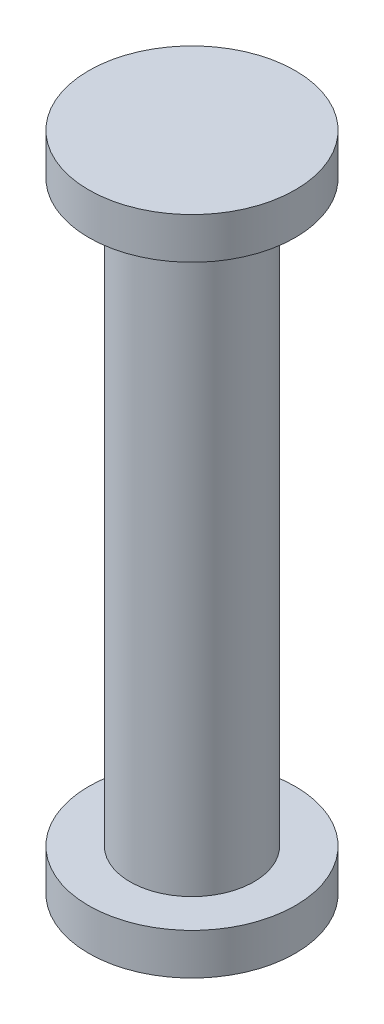
SolidWorks part; units mm, degrees
material "1023 Листовая углеродистая сталь (SS)"
ref_plane "Спереди" through (0, 0, 0) normal (0, 0, 1) x (1, 0, 0)
ref_plane "Сверху" through (0, 0, 0) normal (0, 1, 0) x (1, 0, 0)
ref_plane "Справа" through (0, 0, 0) normal (1, 0, 0) x (0, 0, -1)
sketch "Эскиз1" plane through (0, 0, 0) normal (0, 0, 1) x (1, 0, 0)
  line L0 (0, 0) -> (0, 16)
  line L1 (0, 16) -> (-2.5, 16)
  line L3 (-1.5, 15) -> (-1.5, 1)
  line L4 (-1.5, 1) -> (-2.5, 1)
  line L5 (-2.5, 1) -> (-2.5, 0)
  line L6 (-2.5, 0) -> (0, 0)
  line L7 (-2.5, 16) -> (-2.5, 15)
  line L8 (-2.5, 15) -> (-1.5, 15)
  dimension "D1" = 16
  dimension "D2" = 1
  dimension "D3" = 2.5
  dimension "D4" = 1.5
revolve "Повернуть1" add sketch "Эскиз1" angle 360 about L0
